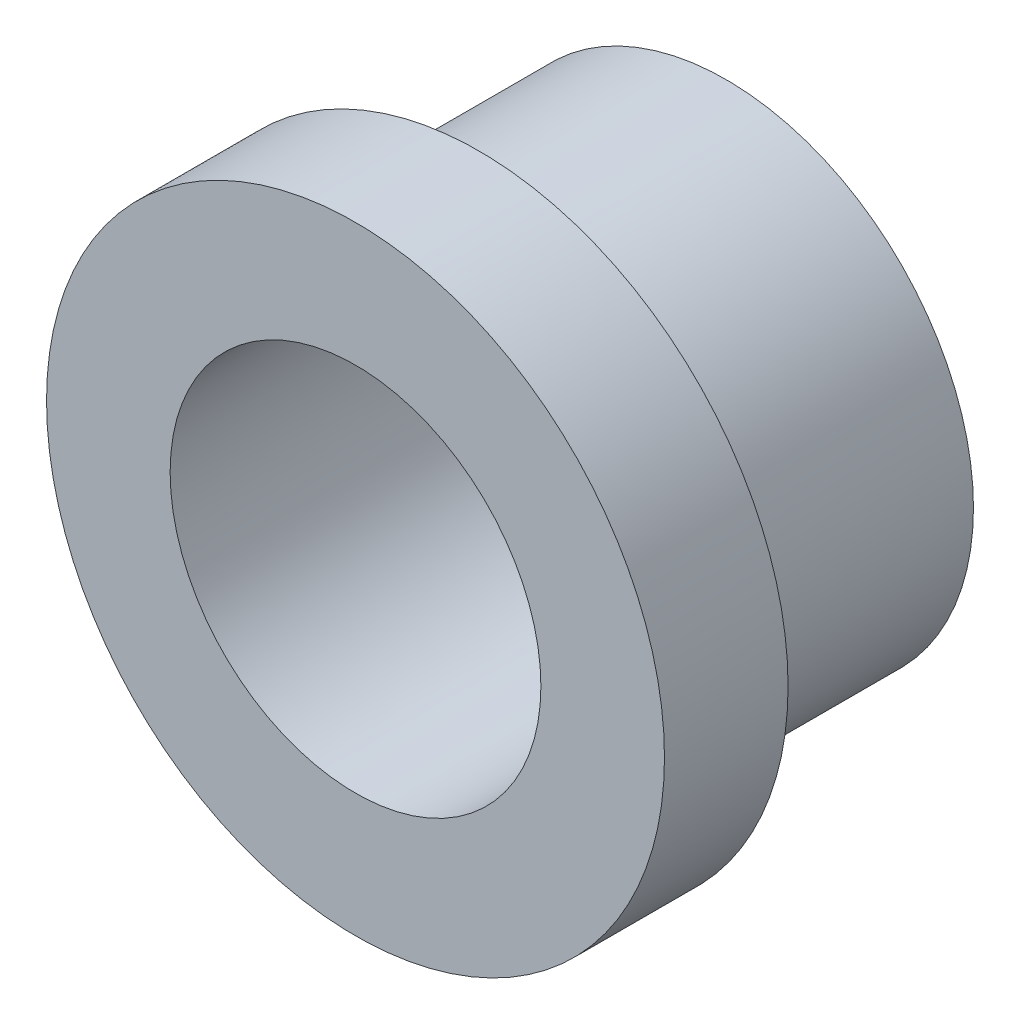
SolidWorks part; units mm, degrees
material "Delrin 2700 NC010, Low Viscosity Acetal Copolymer (SS)"
ref_plane "Front Plane" through (0, 0, 0) normal (0, 0, 1) x (1, 0, 0)
ref_plane "Top Plane" through (0, 0, 0) normal (0, 1, 0) x (1, 0, 0)
ref_plane "Right Plane" through (0, 0, 0) normal (1, 0, 0) x (0, 0, -1)
sketch "Sketch1" plane through (0, 0, 0) normal (1, 0, 0) x (0, 0, -1)
  line L0 (0, 0) -> (10124.8316, 0) construction
  line L1 (0, 7.9375) -> (3.175, 7.9375)
  line L2 (3.175, 7.9375) -> (3.175, 6.35)
  line L3 (3.175, 6.35) -> (9.525, 6.35)
  line L4 (9.525, 6.35) -> (9.525, 4.7625)
  line L5 (9.525, 4.7625) -> (0, 4.7625)
  line L6 (0, 4.7625) -> (0, 7.9375)
  dimension "D1" = 3.175
  dimension "D2" = 4.7625
  dimension "D3" = 1.5875
  dimension "D4" = 1.5875
  dimension "D5" = 9.525
revolve "Revolve1" add sketch "Sketch1" angle 360 about L0
